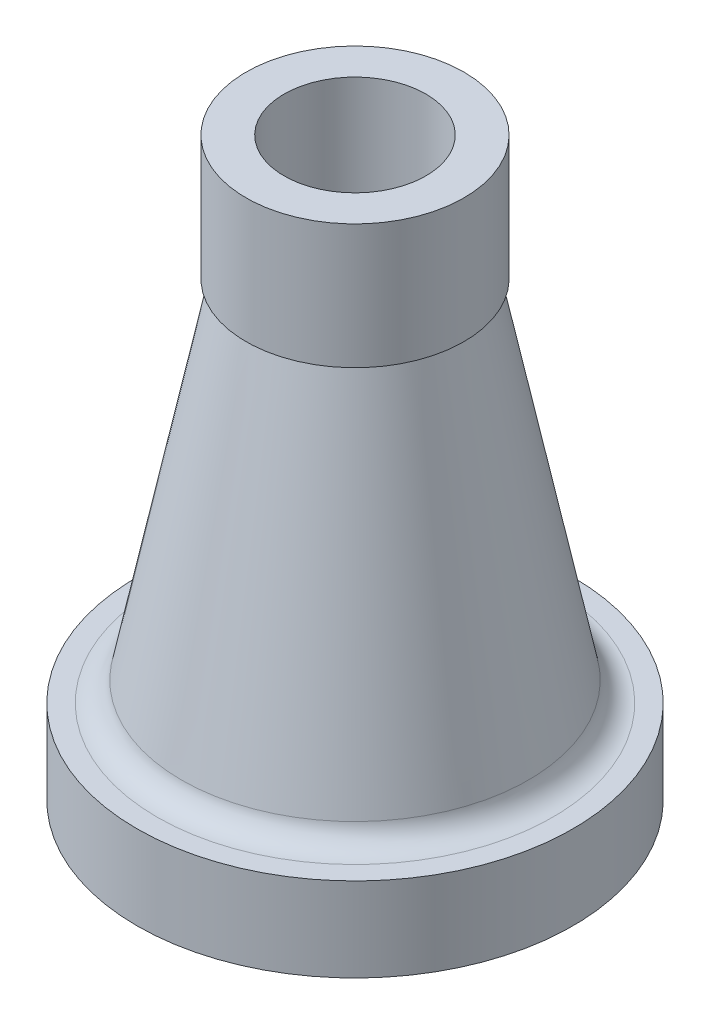
SolidWorks part; units mm, degrees
ref_plane "Front Plane" through (0, 0, 0) normal (0, 0, 1) x (1, 0, 0)
ref_plane "Top Plane" through (0, 0, 0) normal (0, 1, 0) x (1, 0, 0)
ref_plane "Right Plane" through (0, 0, 0) normal (1, 0, 0) x (0, 0, -1)
sketch "Sketch1" plane through (0, 0, 0) normal (0, 0, 1) x (1, 0, 0)
  line L0 (-70, 0) -> (-70, 27)
  line L1 (-70, 27) -> (-63.5367, 27)
  line L2 (-55.6972, 33.4055) -> (-33, 145)
  line L3 (-33, 145) -> (-35, 145)
  line L4 (-35, 145) -> (-35, 185)
  line L5 (-35, 185) -> (-22.7847, 185)
  line L6 (-22.7847, 185) -> (-22.7847, 130)
  line L7 (-22.7847, 130) -> (-47.5982, 8)
  line L8 (-47.5982, 8) -> (-50, 8)
  line L9 (-50, 8) -> (-50, 0)
  line L10 (-50, 0) -> (-70, 0)
  line L11 (0, 0) -> (0, 94.2594) construction
  arc A0 (-63.5367, 27) -> (-55.6972, 33.4055) centre (-63.5367, 35) ccw
  point P10 (-57, 27)
  dimension "D4" = 8
  dimension "D1" = 70
  dimension "D2" = 57
  dimension "D3" = 27
  dimension "D5" = 33
  dimension "D6" = 35
  dimension "D7" = 185
  dimension "D8" = 40
  dimension "D9" = 8
  dimension "D10" = 13
  dimension "D11" = 130
  dimension "D12" = 50
revolve "Revolve1" add sketch "Sketch1" angle 360 about L11
